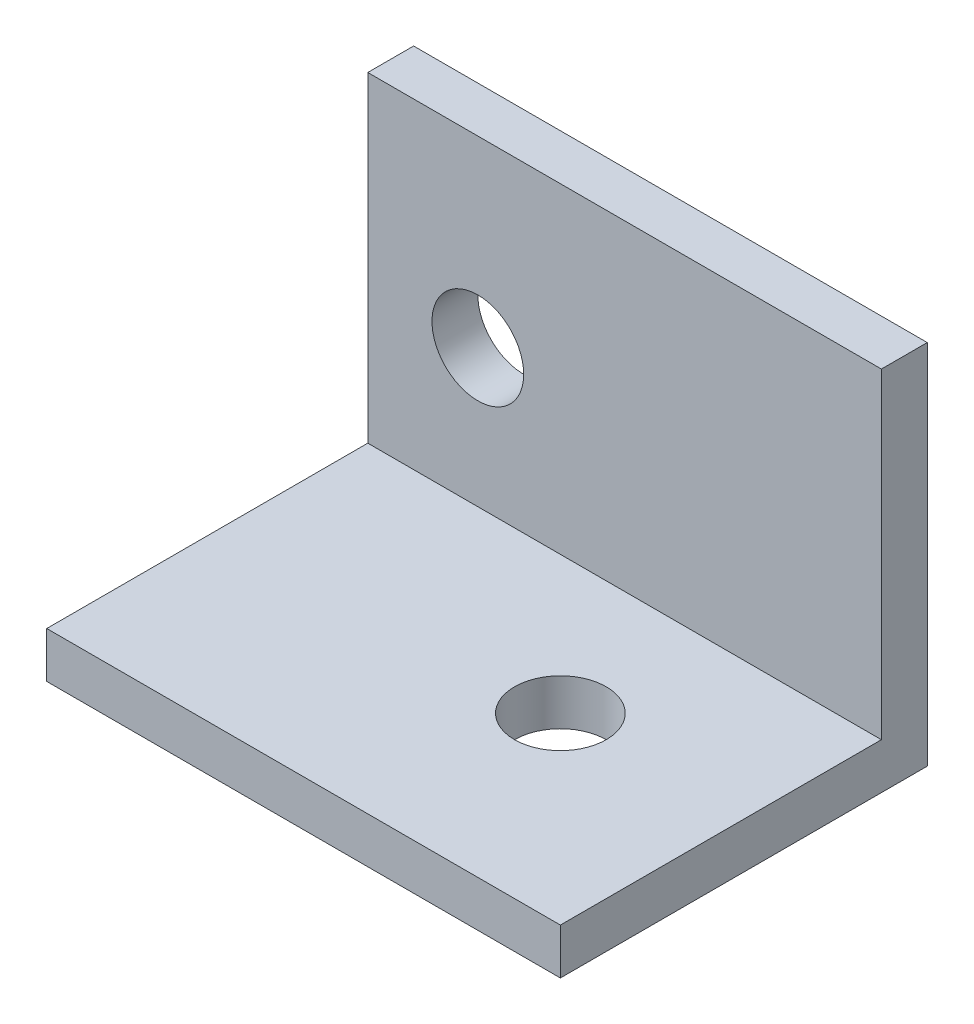
SolidWorks part; units mm, degrees
material "6061-T6 (SS)"
ref_plane "Front Plane" through (0, 0, 0) normal (0, 0, 1) x (1, 0, 0)
ref_plane "Top Plane" through (0, 0, 0) normal (0, 1, 0) x (1, 0, 0)
ref_plane "Right Plane" through (0, 0, 0) normal (1, 0, 0) x (0, 0, -1)
sketch "Sketch1" plane through (0, 0, 0) normal (0, 1, 0) x (1, 0, 0)
  line L1 (-17.78, -12.7) -> (17.78, -12.7)
  line L2 (-17.78, -12.7) -> (-17.78, 12.7)
  line L3 (-17.78, 12.7) -> (17.78, 12.7)
  line L4 (17.78, -12.7) -> (17.78, 12.7)
  line L5 (-17.78, -12.7) -> (17.78, 12.7) construction
  line L6 (-17.78, 12.7) -> (17.78, -12.7) construction
  point P0 (0, 0)
  dimension "D1" = 25.4
  dimension "D2" = 35.56
extrude "Boss-Extrude1" add sketch "Sketch1" along normal blind 3.175
sketch "Sketch2" plane through (0, 3.175, 0) normal (0, 1, 0) x (1, 0, 0)
  line L0 (-17.78, 12.7) -> (-17.78, -12.7) construction
  line L1 (17.78, 12.7) -> (-17.78, 12.7)
  line L2 (17.78, 12.7) -> (17.78, 9.525)
  line L3 (17.78, 9.525) -> (-17.78, 9.525)
  line L4 (-17.78, 12.7) -> (-17.78, 9.525)
extrude "Boss-Extrude2" add sketch "Sketch2" along normal blind 22.225
sketch "Sketch3" plane through (0, 3.175, 0) normal (0, 1, 0) x (1, 0, 0)
  line L0 (17.78, -12.7) -> (17.78, 9.525) construction
  line L1 (-17.78, -12.7) -> (17.78, -12.7) construction
  circle A0 centre (5.08, 0) radius 3.175
  dimension "D1" = 12.7
  dimension "D3" = 6.35
  dimension "D2" = 12.7
extrude "Cut-Extrude1" cut sketch "Sketch3" against normal blind 3.175
sketch "Sketch4" plane through (0, 0, -9.525) normal (0, 0, 1) x (1, 0, 0)
  line L0 (-17.78, 25.4) -> (-17.78, 3.175) construction
  line L1 (-17.78, 25.4) -> (17.78, 25.4) construction
  circle A0 centre (-10.16, 12.7) radius 3.175
  dimension "D1" = 7.62
  dimension "D2" = 12.7
  dimension "D3" = 6.35
extrude "Cut-Extrude2" cut sketch "Sketch4" against normal blind 3.175
